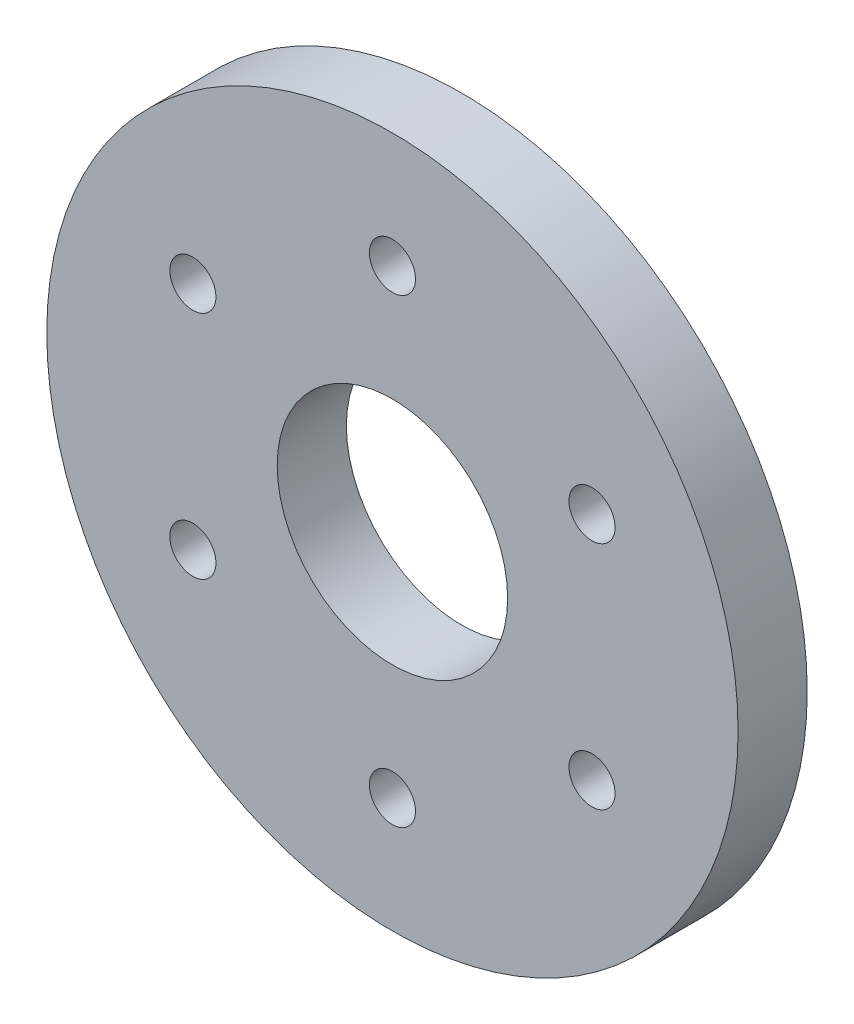
SolidWorks part; units mm, degrees
ref_plane "Front Plane" through (0, 0, 0) normal (0, 0, 1) x (1, 0, 0)
ref_plane "Top Plane" through (0, 0, 0) normal (0, 1, 0) x (1, 0, 0)
ref_plane "Right Plane" through (0, 0, 0) normal (1, 0, 0) x (0, 0, -1)
sketch "Sketch1" plane through (0, 0, 0) normal (0, 0, 1) x (1, 0, 0)
  circle A0 centre (0, 0) radius 30
  circle A1 centre (0, 0) radius 20 construction
  circle A2 centre (0, 0) radius 10
  circle A3 centre (0, 20) radius 2
  circle A4 centre (17.3205, 10) radius 2
  circle A5 centre (17.3205, -10) radius 2
  circle A6 centre (0, -20) radius 2
  circle A7 centre (-17.3205, -10) radius 2
  circle A8 centre (-17.3205, 10) radius 2
  point P19 (0, 0)
  dimension "D1" = 60
  dimension "D2" = 20
  dimension "D3" = 40
  dimension "D4" = 4
  dimension "D5" = 6
extrude "Boss-Extrude1" add sketch "Sketch1" along normal blind 6
